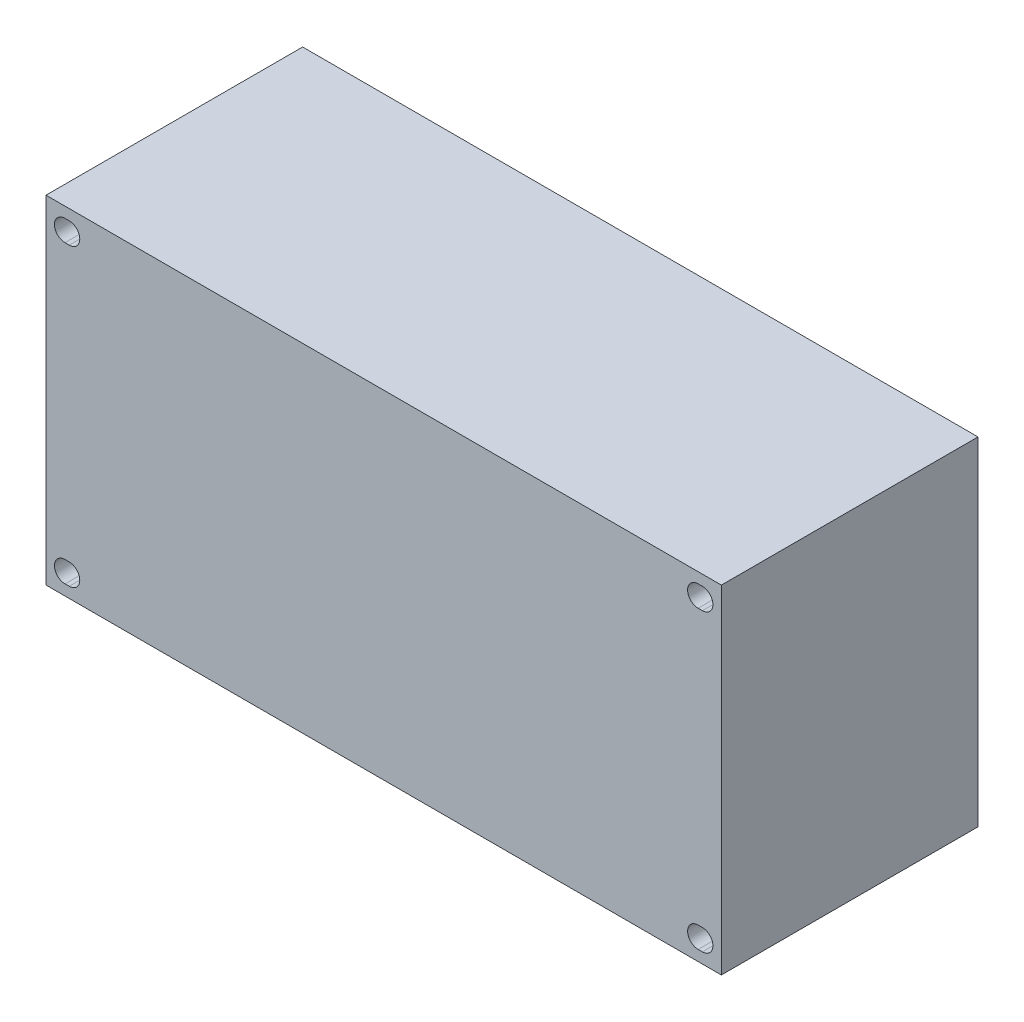
SolidWorks part; units mm, degrees
material "1060 Alloy"
ref_plane "Front Plane" through (0, 0, 0) normal (0, 0, 1) x (1, 0, 0)
ref_plane "Top Plane" through (0, 0, 0) normal (0, 1, 0) x (1, 0, 0)
ref_plane "Right Plane" through (0, 0, 0) normal (1, 0, 0) x (0, 0, -1)
sketch "Sketch1" plane through (0, 0, 0) normal (0, 0, 1) x (1, 0, 0)
  line L1 (-50.8, -25.4) -> (50.8, -25.4)
  line L2 (-50.8, -25.4) -> (-50.8, 25.4)
  line L3 (-50.8, 25.4) -> (50.8, 25.4)
  line L4 (50.8, -25.4) -> (50.8, 25.4)
  line L5 (-50.8, -25.4) -> (50.8, 25.4) construction
  line L6 (-50.8, 25.4) -> (50.8, -25.4) construction
  point P0 (0, 0)
  dimension "D1" = 50.8
  dimension "D2" = 101.6
extrude "Boss-Extrude1" add sketch "Sketch1" along normal blind 38.608
sketch "Sketch4" plane through (0, 0, 38.608) normal (0, 0, 1) x (1, 0, 0)
  line L0 (50.8, 25.4) -> (-50.8, -25.4) construction
  line L1 (49.53, 28.72) -> (49.53, 15.73) construction
  line L2 (-47.625, 22.225) -> (47.625, 22.225) construction
  line L3 (-47.625, 22.225) -> (-47.625, -22.225) construction
  line L4 (-47.625, -22.225) -> (47.625, -22.225) construction
  line L5 (47.625, 22.225) -> (47.625, -22.225) construction
  line L6 (-47.625, 22.225) -> (47.625, -22.225) construction
  line L7 (-47.625, -22.225) -> (47.625, 22.225) construction
  line L8 (47.3075, 22.225) -> (47.9425, 22.225) construction
  line L9 (47.3075, 23.8125) -> (47.9425, 23.8125)
  line L10 (47.3075, 20.6375) -> (47.9425, 20.6375)
  line L11 (45.72, 16.7444) -> (45.72, 27.7056) construction
  arc A0 (47.3075, 23.8125) -> (47.3075, 20.6375) centre (47.3075, 22.225) ccw
  arc A1 (47.9425, 20.6375) -> (47.9425, 23.8125) centre (47.9425, 22.225) ccw
  point P4 (0, 0)
  point P12 (47.625, 22.225)
  point P20 (49.53, 22.225)
  point P23 (45.72, 22.225)
  dimension "D3" = 1.5875
  dimension "D1" = 44.45
  dimension "D2" = 95.25
  dimension "D4" = 3.81
extrude "Cut-Extrude1" cut sketch "Sketch4" against normal through all
mirror "Mirror1" about plane through (0, 0, 0) normal (0, 1, 0) of "Cut-Extrude1"
mirror "Mirror2" about plane through (0, 0, 0) normal (1, 0, 0) of "Mirror1", "Cut-Extrude1"
